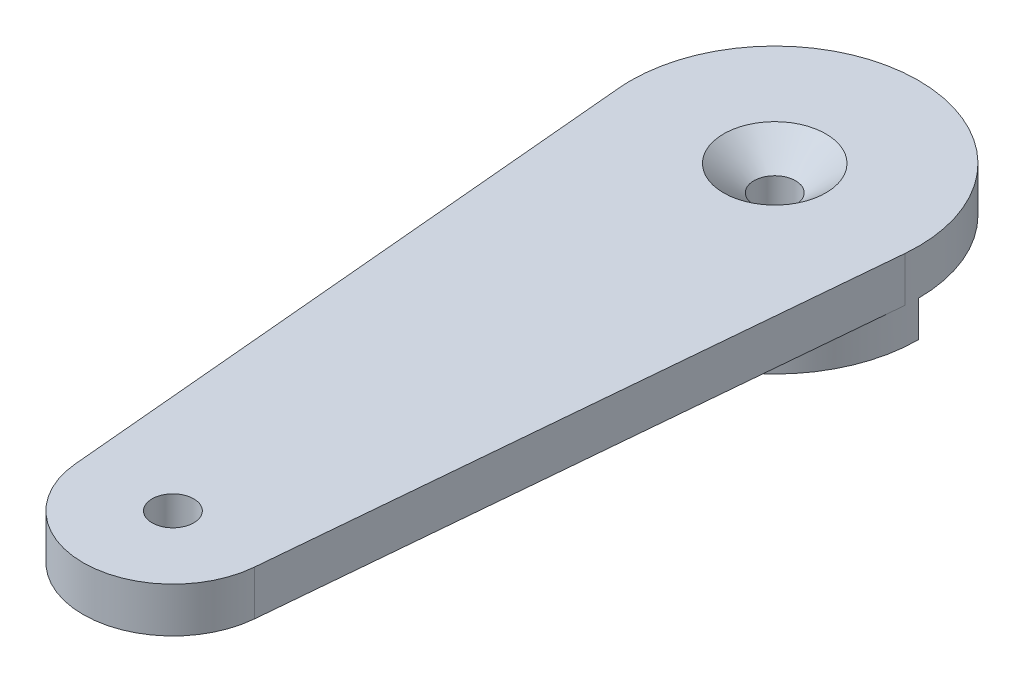
SolidWorks part; units mm, degrees
ref_plane "Front Plane" through (0, 0, 0) normal (0, 0, 1) x (1, 0, 0)
ref_plane "Top Plane" through (0, 0, 0) normal (0, 1, 0) x (1, 0, 0)
ref_plane "Right Plane" through (0, 0, 0) normal (1, 0, 0) x (0, 0, -1)
sketch "Sketch1" plane through (0, 0, 0) normal (0, 1, 0) x (1, 0, 0)
  line L0 (-10.1192, -0.9099) -> (-6.3245, -43.1137)
  line L1 (6.3245, -43.1137) -> (10.1192, -0.9099)
  line L2 (0, 0) -> (0, -42.545) construction
  arc A0 (-10.1192, -0.9099) -> (10.1192, -0.9099) centre (0, 0) cw
  arc A1 (-6.3245, -43.1137) -> (6.3245, -43.1137) centre (0, -42.545) ccw
  circle A5 centre (0, -42.545) radius 1.4732
  dimension "D1" = 2.9464
  dimension "D2" = 6.35
  dimension "D3" = 10.16
  dimension "D4" = 42.545
extrude "Boss-Extrude1" add sketch "Sketch1" along normal blind 3.175
sketch "Sketch2" plane through (0, 0, 0) normal (0, -1, 0) x (1, 0, 0)
  line L0 (7.62, 0) -> (10.16, 0)
  line L1 (-10.16, 0) -> (-7.62, 0)
  arc A0 (-7.62, 0) -> (7.62, 0) centre (0, 0) ccw
  arc A1 (-10.1192, 0.9099) -> (10.1192, 0.9099) centre (0, 0) ccw construction
  arc A2 (10.16, 0) -> (-10.16, 0) centre (0, 0) ccw
  arc A3 (-10.1192, 0.9099) -> (10.1192, 0.9099) centre (0, 0) ccw construction
  dimension "D1" = 2.54
extrude "Boss-Extrude2" add sketch "Sketch2" along normal blind 2.54
sketch "Sketch4" plane through (0, -2.54, 0) normal (0, -1, 0) x (1, 0, 0)
  circle A0 centre (0, 0) radius 3.1115
  dimension "D1" = 6.223
extrude "Boss-Extrude3" [suppressed] add sketch "Sketch4" along normal blind 1.9685
hole_wizard "CSK for #4 Flat Head Machine Screw (100)1" positions "Sketch5" profile "Sketch6" countersink size "#4" standard "ANSI Inch" end condition through all
sketch "Sketch5" plane through (0, 3.175, 0) normal (0, 1, 0) x (1, 0, 0)
  point P0 (0, 0)
sketch "Sketch6" plane through (0, 3.175, 0) normal (1, 0, 0) x (0, 0, 1)
  line L0 (0, 0) -> (0, 5.715)
  line L1 (0, 5.715) -> (1.4732, 5.715)
  line L2 (1.4732, 5.715) -> (1.4732, 1.7966)
  line L3 (1.4732, 1.7966) -> (3.6143, 0)
  line L5 (3.6143, 0) -> (0, 0)
  line L6 (-1.4732, 1.7966) -> (-3.6143, 0) construction
  line L11 (0, -6.35) -> (0, 107.95) construction
  dimension "Thru Hole Dia." = 2.9464
  dimension "Thru Hole Depth" = 5.715
  dimension "Near C'Sink Dia." = 7.2285
  dimension "Near C'Sink Angle" = 100
